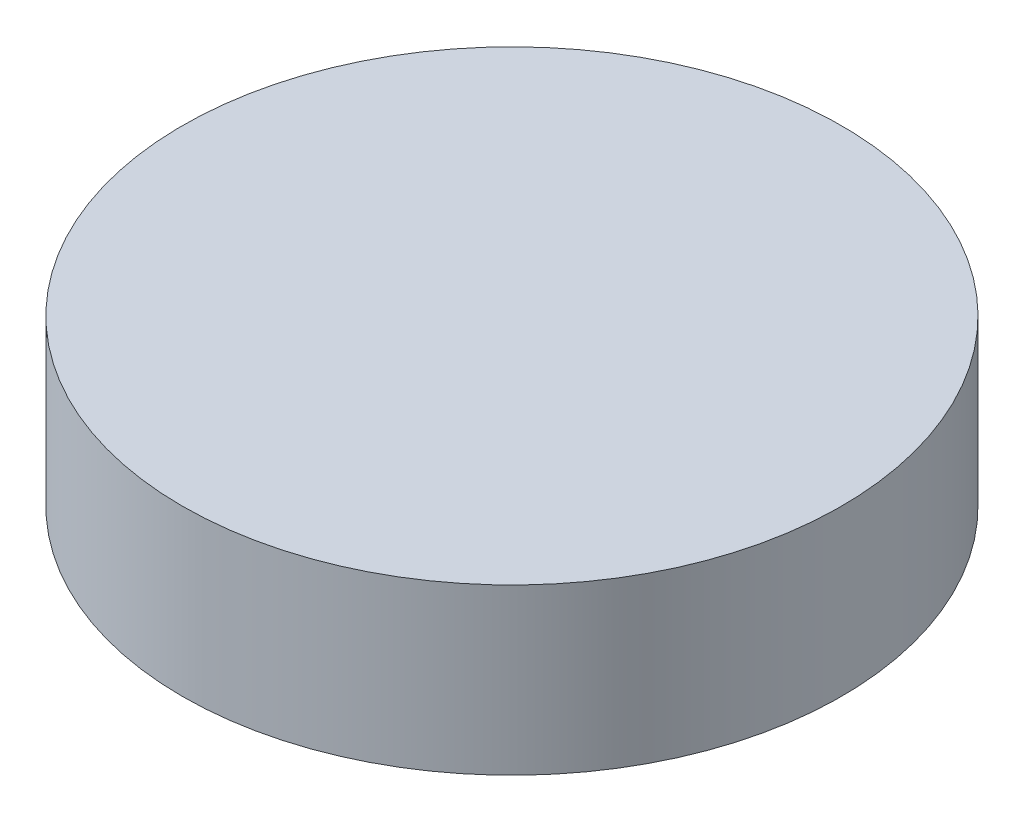
SolidWorks part; units mm, degrees
ref_plane "Front Plane" through (0, 0, 0) normal (0, 0, 1) x (1, 0, 0)
ref_plane "Top Plane" through (0, 0, 0) normal (0, 1, 0) x (1, 0, 0)
ref_plane "Right Plane" through (0, 0, 0) normal (1, 0, 0) x (0, 0, -1)
sketch "Sketch1" plane through (0, 0, 0) normal (0, 1, 0) x (1, 0, 0)
  circle A0 centre (0, 0) radius 50.8
extrude "Boss-Extrude1" add sketch "Sketch1" along normal blind 25.4
